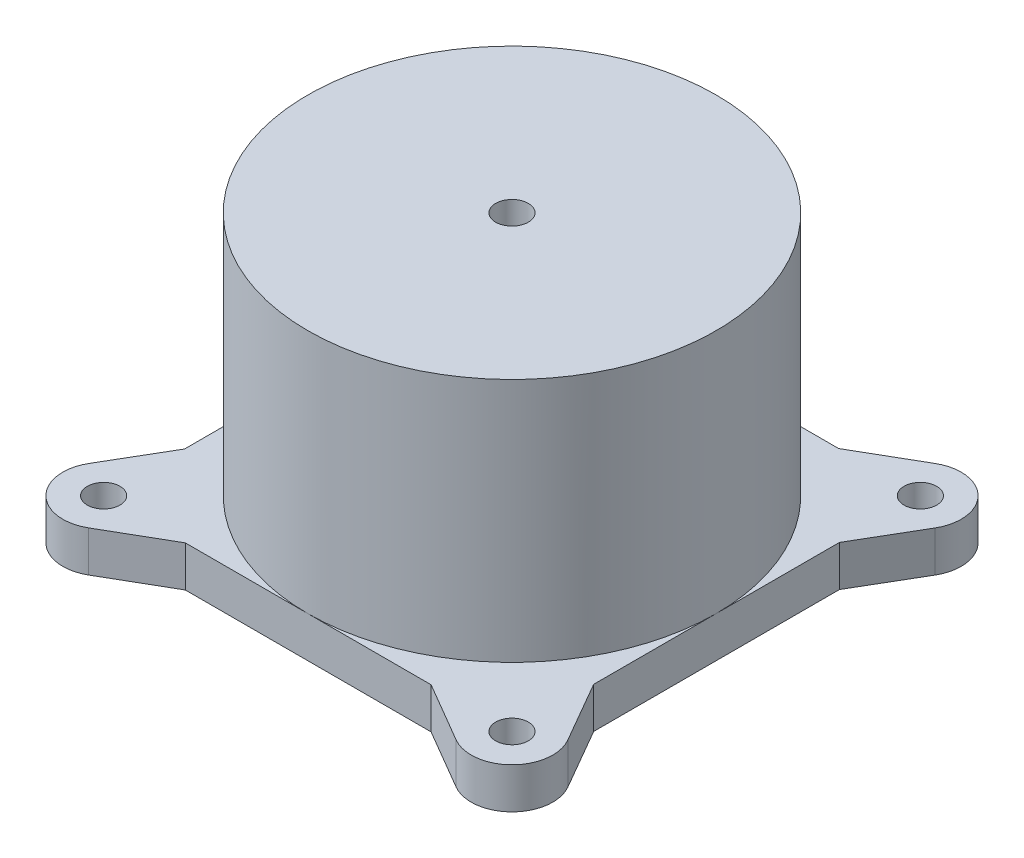
SolidWorks part; units mm, degrees
ref_plane "Front Plane" through (0, 0, 0) normal (0, 0, 1) x (1, 0, 0)
ref_plane "Top Plane" through (0, 0, 0) normal (0, 1, 0) x (1, 0, 0)
ref_plane "Right Plane" through (0, 0, 0) normal (1, 0, 0) x (0, 0, -1)
sketch "Sketch1" plane through (0, 0, 0) normal (0, 1, 0) x (1, 0, 0)
  circle A0 centre (0, 0) radius 50
  circle A1 centre (0, 0) radius 4
  dimension "D1" = 100
extrude "Boss-Extrude1" add sketch "Sketch1" along normal blind 10
sketch "Sketch2" plane through (0, 0, 0) normal (0, -1, 0) x (1, 0, 0)
  circle A0 centre (0, 0) radius 50
  circle A1 centre (0, 0) radius 40
extrude "Boss-Extrude2" add sketch "Sketch2" along normal blind 50
sketch "Sketch4" plane through (0, -50, 0) normal (0, -1, 0) x (1, 0, 0)
  line L0 (0, 70.5775) -> (0, -77.3171) construction
  line L3 (-30.1867, -50) -> (29.9974, -50)
  line L5 (-49.2514, 49.2514) -> (47.1716, -47.1716) construction
  line L6 (-50, -50) -> (42.9289, 42.9289) construction
  line L7 (-58.6606, -45.0006) -> (-50, -29.9974)
  line L8 (-44.9529, -58.6329) -> (-30.1867, -50)
  line L9 (-45.0006, 58.6606) -> (-29.9974, 50)
  line L10 (-58.6329, 44.9529) -> (-50, 30.1867)
  line L11 (58.6606, 45.0006) -> (50, 29.9974)
  line L12 (44.9529, 58.6329) -> (30.1867, 50)
  line L13 (45.0006, -58.6606) -> (29.9974, -50)
  line L14 (58.6329, -44.9529) -> (50, -30.1867)
  line L15 (-29.9974, 50) -> (30.1867, 50)
  line L16 (-50, 30.1867) -> (-50, -29.9974)
  line L17 (50, 29.9974) -> (50, -30.1867)
  circle A0 centre (-50, 50) radius 4
  circle A1 centre (-50, -50) radius 4
  circle A2 centre (50, -50) radius 4
  circle A3 centre (50, 50) radius 4
  arc A4 (-58.6606, -45.0006) -> (-44.9529, -58.6329) centre (-50, -50) ccw
  arc A5 (-45.0006, 58.6606) -> (-58.6329, 44.9529) centre (-50, 50) ccw
  arc A6 (58.6606, 45.0006) -> (44.9529, 58.6329) centre (50, 50) ccw
  arc A7 (45.0006, -58.6606) -> (58.6329, -44.9529) centre (50, -50) ccw
  circle A8 centre (0, 0) radius 40
  point P0 (0, 0)
  point P38 (0, 0)
  dimension "D3" = 8
  dimension "D4" = 8
  dimension "D5" = 20
  dimension "D1" = 100
  dimension "D2" = 100
  dimension "D6" = 4
extrude "Boss-Extrude3" add sketch "Sketch4" along normal blind 10
